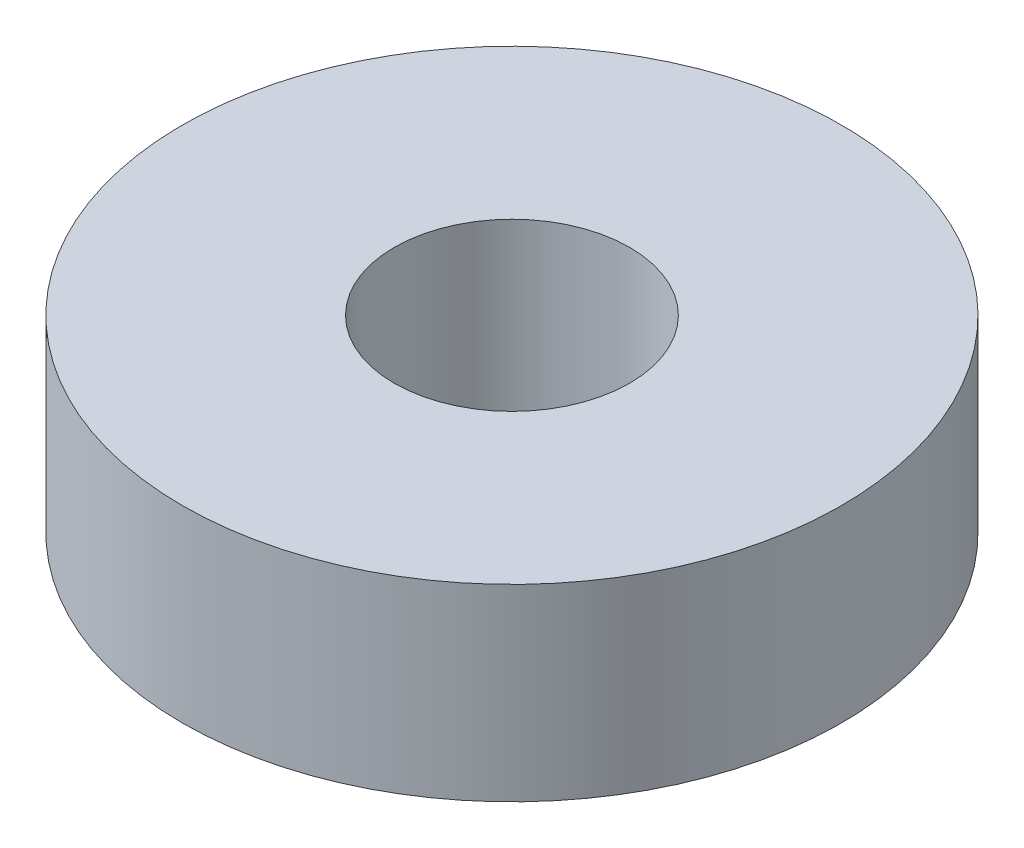
SolidWorks part; units mm, degrees
ref_plane "Alzado" through (0, 0, 0) normal (0, 0, 1) x (1, 0, 0)
ref_plane "Planta" through (0, 0, 0) normal (0, 1, 0) x (1, 0, 0)
ref_plane "Vista lateral" through (0, 0, 0) normal (1, 0, 0) x (0, 0, -1)
sketch "Croquis1" plane through (0, 0, 0) normal (0, 1, 0) x (1, 0, 0)
  circle A0 centre (0, 0) radius 14
  circle A1 centre (0, 0) radius 5
  dimension "D1" = 28
  dimension "D2" = 10
extrude "Saliente-Extruir1" add sketch "Croquis1" along normal blind 8
